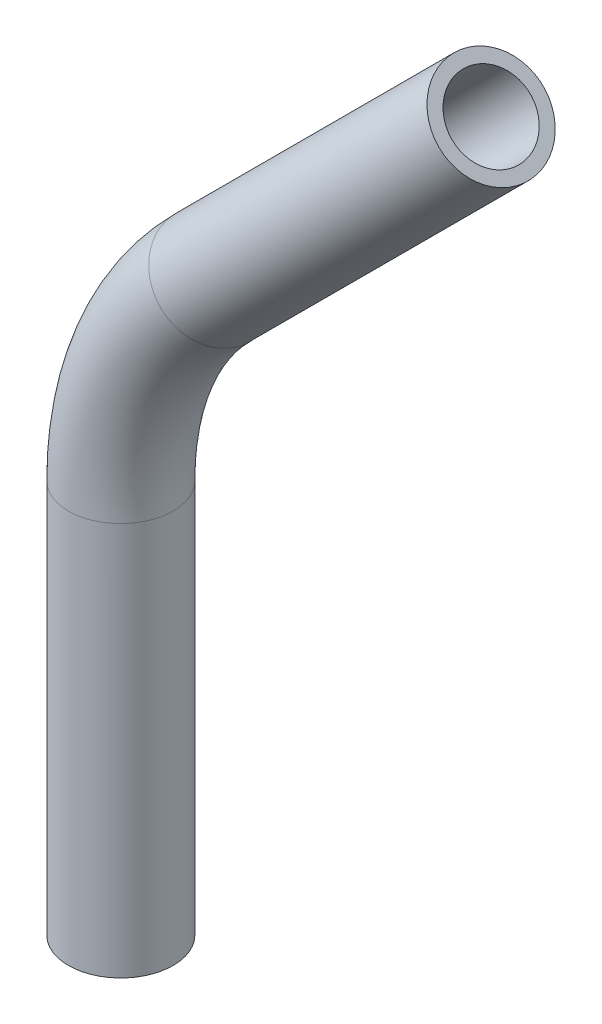
SolidWorks part; units mm, degrees
ref_plane "Front Plane" through (0, 0, 0) normal (0, 0, 1) x (1, 0, 0)
ref_plane "Top Plane" through (0, 0, 0) normal (0, 1, 0) x (1, 0, 0)
ref_plane "Right Plane" through (0, 0, 0) normal (1, 0, 0) x (0, 0, -1)
sketch "Sketch1" plane through (0, 0, 0) normal (0, 0, 1) x (1, 0, 0)
  line L0 (0, 0) -> (0, 30.0589)
  line L1 (7.0294, 47.0294) -> (28.2843, 68.2843)
  line L2 (0, 0) -> (0, 77.216) construction
  line L3 (0, -4.4) -> (0, 4.4) construction
  arc A0 (0, 30.0589) -> (7.0294, 47.0294) centre (24, 30.0589) cw
  point P6 (0, 40)
  dimension "D3" = 24
  dimension "D1" = 40
  dimension "D2" = 40
  dimension "D4" = 135
  dimension "D5" = 45
sketch "Sketch2" plane through (0, 0, 0) normal (0, 1, 0) x (1, 0, 0)
  circle A0 centre (0, 0) radius 4
  circle A1 centre (0, 0) radius 3
  dimension "D1" = 6
  dimension "D2" = 8
sweep "Sweep1" add profiles "Sketch2" path "Sketch1"
